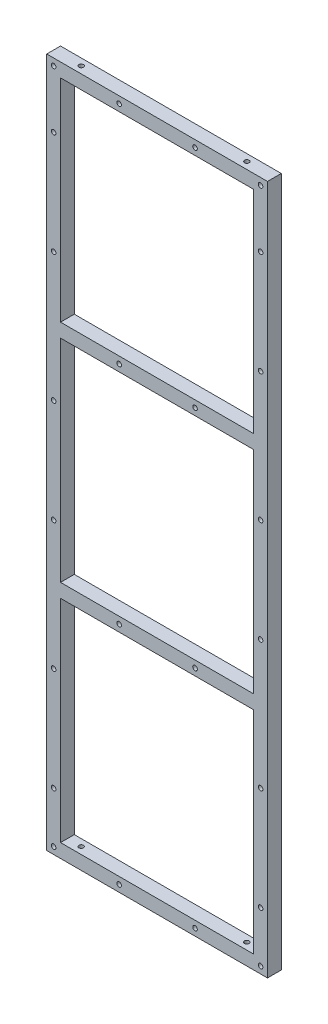
SolidWorks part; units mm, degrees
material "Alumina"
ref_plane "Front Plane" through (0, 0, 0) normal (0, 0, 1) x (1, 0, 0)
ref_plane "Top Plane" through (0, 0, 0) normal (0, 1, 0) x (1, 0, 0)
ref_plane "Right Plane" through (0, 0, 0) normal (1, 0, 0) x (0, 0, -1)
sketch "Sketch1" plane through (0, 0, 0) normal (0, 0, 1) x (1, 0, 0)
  line L0 (42, 144) -> (42, 52)
  line L9 (-48, -150) -> (48, -150)
  line L10 (-48, -150) -> (-48, 150)
  line L11 (-48, 150) -> (48, 150)
  line L12 (48, -150) -> (48, 150)
  line L14 (0, 0) -> (0, 46) construction
  line L15 (-42, -144) -> (42, -144)
  line L17 (-42, 144) -> (42, 144)
  line L19 (-42, 46) -> (-42, -46)
  line L20 (-42, -52) -> (-42, -144)
  line L21 (-42, 52) -> (42, 52)
  line L23 (-42, 46) -> (42, 46)
  line L25 (-42, -46) -> (42, -46)
  line L27 (-42, -52) -> (42, -52)
  line L33 (42, 46) -> (42, -46)
  line L34 (-42, 52) -> (-42, 144)
  line L36 (42, -52) -> (42, -144)
  dimension "D1" = 96
  dimension "D2" = 6
  dimension "D3" = 84
  dimension "D4" = 92
  dimension "D5" = 6
  dimension "D6" = 92
  dimension "D7" = 6
  dimension "D8" = 92
  dimension "D9" = 46
  dimension "D10" = 6
  dimension "D12" = 6
extrude "Boss-Extrude1" add sketch "Sketch1" along normal blind 6
sketch "Sketch2" plane through (0, 0, 6) normal (0, 0, 1) x (1, 0, 0)
  line L0 (-48, 150) -> (-42, 144) construction
  line L1 (42, 144) -> (48, 150) construction
  line L2 (42, -144) -> (48, -150) construction
  line L3 (-42, -144) -> (-48, -150) construction
  line L4 (-45, 147) -> (-45, 49) construction
  circle A0 centre (-45, 147) radius 1
  circle A1 centre (45, 147) radius 1
  circle A2 centre (-45, 49) radius 1
  circle A3 centre (45, 49) radius 1
  circle A4 centre (-45, -49) radius 1
  circle A5 centre (45, -49) radius 1
  circle A6 centre (-45, -147) radius 1
  circle A7 centre (45, -147) radius 1
  dimension "D1" = 2
  dimension "D5" = 2
  dimension "D3" = 98
  dimension "D2" = 4
extrude "Cut-Extrude1" cut sketch "Sketch2" against normal blind 6
sketch "Sketch3" plane through (0, 0, 6) normal (0, 0, 1) x (1, 0, 0)
  line L0 (48, 150) -> (-48, 150) construction
  line L1 (-48, 150) -> (-48, -150) construction
  line L2 (-45, 122) -> (45, 122) construction
  line L3 (-16.5, 147) -> (-16.5, 49) construction
  line L4 (-45, 122) -> (-45, 77) construction
  line L5 (-45, 122) -> (-45, 21) construction
  circle A0 centre (-45, 122) radius 1
  circle A12 centre (-16.5, 147) radius 1
  circle A19 centre (16.5, 147) radius 1
  circle A20 centre (-16.5, 49) radius 1
  circle A21 centre (16.5, 49) radius 1
  circle A22 centre (-16.5, -49) radius 1
  circle A23 centre (16.5, -49) radius 1
  circle A24 centre (-16.5, -147) radius 1
  circle A25 centre (16.5, -147) radius 1
  circle A26 centre (-45, 21) radius 1
  circle A27 centre (45, 122) radius 1
  circle A28 centre (45, 77) radius 1
  circle A29 centre (-45, 77) radius 1
  circle A30 centre (45, 21) radius 1
  circle A31 centre (45, -24) radius 1
  circle A32 centre (-45, -24) radius 1
  circle A33 centre (-45, -80) radius 1
  circle A34 centre (45, -80) radius 1
  circle A35 centre (45, -125) radius 1
  circle A36 centre (-45, -125) radius 1
  dimension "D1" = 28
  dimension "D6" = 2
  dimension "D3" = 2
  dimension "D8" = 3
  dimension "D9" = 33
  dimension "D10" = 31.5
  dimension "D12" = 2
  dimension "D13" = 45
  dimension "D14" = 3
  dimension "D2" = 90
  dimension "D7" = 3
  dimension "D11" = 98
  dimension "D16" = 101
  dimension "D4" = 2
  dimension "D5" = 2
  dimension "D15" = 3
sketch "Sketch4" plane through (0, 150, 0) normal (0, 1, 0) x (1, 0, 0)
  line L0 (48, 0) -> (-48, 0) construction
  line L1 (-48, -6) -> (-48, 0) construction
  line L2 (0, -3.3) -> (0, 3.3) construction
  circle A0 centre (-36, -3) radius 1
  circle A1 centre (36, -3) radius 1
  dimension "D1" = 3
  dimension "D3" = 2
  dimension "D2" = 12
extrude "Cut-Extrude5" cut sketch "Sketch4" against normal blind 10
mirror "Mirror1" about plane through (0, 0, 0) normal (0, 1, 0) of "Cut-Extrude5"
extrude "Cut-Extrude6" cut sketch "Sketch3" against normal blind 10
